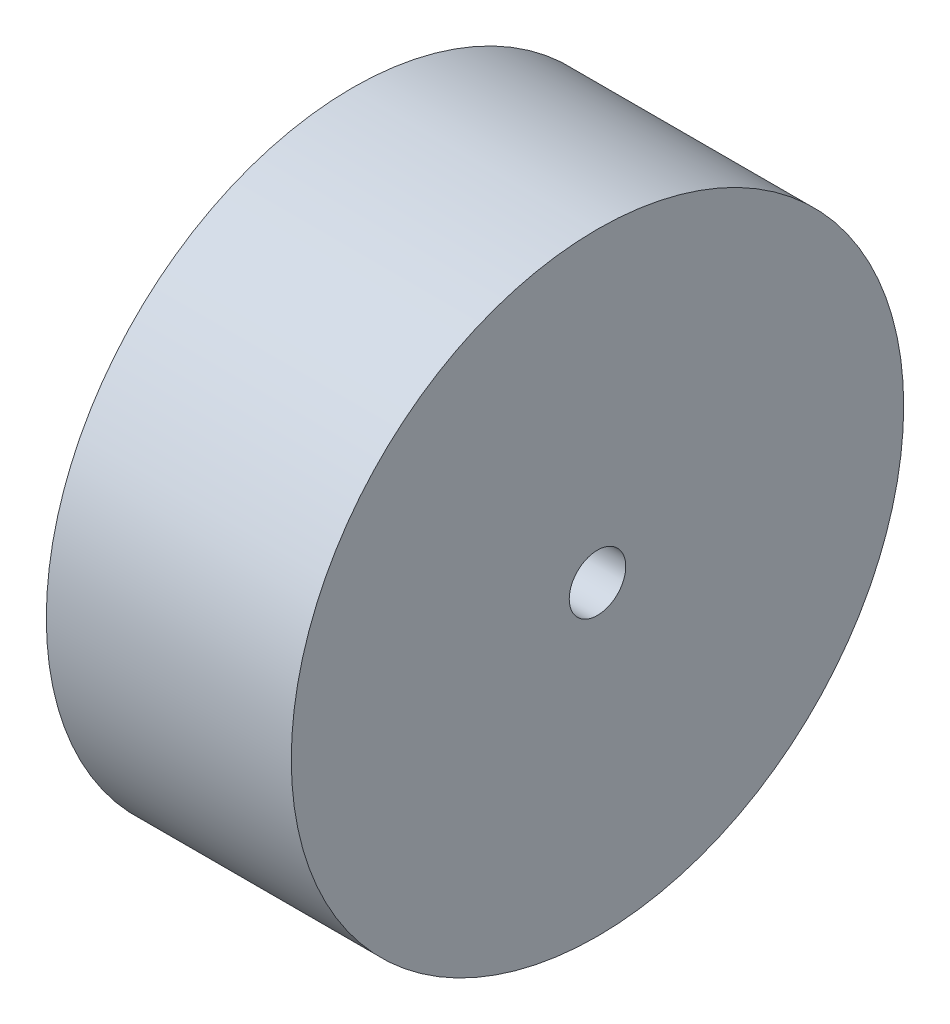
SolidWorks part; units mm, degrees
ref_plane "前视基准面" through (0, 0, 0) normal (0, 0, 1) x (1, 0, 0)
ref_plane "上视基准面" through (0, 0, 0) normal (0, 1, 0) x (1, 0, 0)
ref_plane "右视基准面" through (0, 0, 0) normal (1, 0, 0) x (0, 0, -1)
other "Configuration Table"
sketch "草图1" plane through (0, 0, 0) normal (1, 0, 0) x (0, 0, -1)
  circle A0 centre (0, 0) radius 32.5
  circle A1 centre (0, 0) radius 3
  dimension "D1" = 65
  dimension "D2" = 6
extrude "凸台-拉伸1" add sketch "草图1" along normal blind 26 contours A0 | A1
